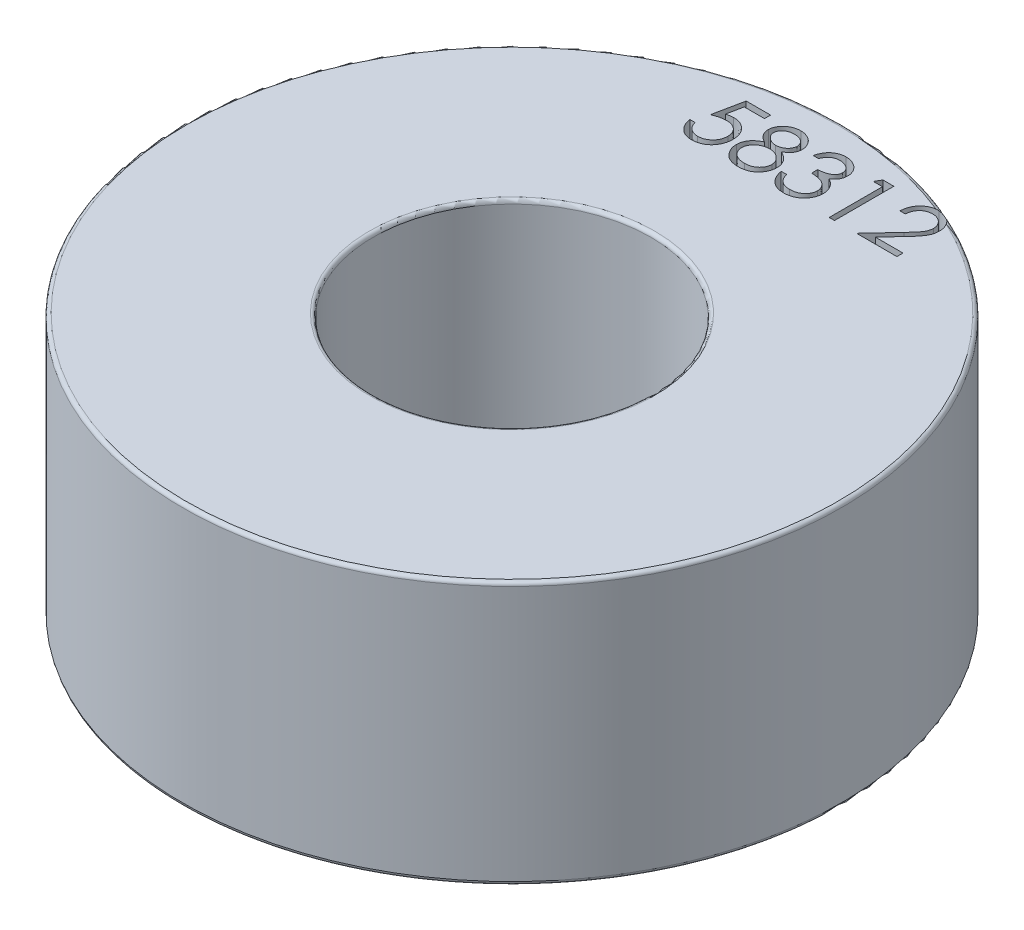
SolidWorks part; units mm, degrees
ref_plane "Front Plane" through (0, 0, 0) normal (0, 0, 1) x (1, 0, 0)
ref_plane "Top Plane" through (0, 0, 0) normal (0, 1, 0) x (1, 0, 0)
ref_plane "Right Plane" through (0, 0, 0) normal (1, 0, 0) x (0, 0, -1)
sketch "Toroidal Core TC229" plane through (0, 0, 0) normal (0, 0, 1) x (1, 0, 0)
  line L0 (0, -8.108) -> (0, 13.3131) construction
  line L2 (5.7191, 0) -> (13.073, 0)
  line L3 (5.573, 0.1461) -> (5.573, 10.3979)
  line L4 (5.7191, 10.5439) -> (13.073, 10.5439)
  line L5 (13.2191, 0.1461) -> (13.2191, 10.3979)
  arc A0 (5.7191, 0) -> (5.573, 0.1461) centre (5.7191, 0.1461) cw
  arc A1 (13.073, 0) -> (13.2191, 0.1461) centre (13.073, 0.1461) ccw
  arc A2 (13.073, 10.5439) -> (13.2191, 10.3979) centre (13.073, 10.3979) cw
  arc A3 (5.573, 10.3979) -> (5.7191, 10.5439) centre (5.7191, 10.3979) cw
  point P9 (5.573, 0)
  point P12 (13.2191, 0)
  point P15 (13.2191, 10.5439)
  point P18 (5.573, 10.5439)
  dimension "D4" = 0.1461
  dimension "D1" = 7.3539
  dimension "D2" = 10.5439
  dimension "D3" = 5.573
revolve "Revolve2" add sketch "Toroidal Core TC229" angle 360 about L0
sketch "Sketch1" plane through (0, 10.5439, 0) normal (0, 1, 0) x (1, 0, 0)
  text T0 "58312" font "Century Gothic" height in points 9
extrude "Cut-Extrude1" cut sketch "Sketch1" against normal blind 1
equation "\"FinishedODmax\"  = 23.7mm"
equation "\"FinishedIDmin\"  = 13.3mm"
equation "\"FinishedHTmax\"  = 8.39mm"
equation "\"FinishedInnerRadiusmin\"= \"FinishedIDmin\" / 2"
equation "\"FinishedOuterRadiusmin\"= \"FinishedODmax\" / 2"
equation "\"Dia18AWG\"= .0424in'Single Build Magnet Wire per http://www.mwswire.com/pdf_files/mws_tech_book/page4_5_6_33_34.pdf"
equation "\"HT\"= \"FinishedHTmax\" + ( \"Dia18AWG\" * 2 )"
equation "\"InnerRadius\"  = \"FinishedInnerRadiusmin\" - ( \"Dia18AWG\" * 1 )"
equation "\"OuterRadius\" = \"FinishedOuterRadiusmin\" + ( \"Dia18AWG\" * 1 )"
equation "\"D2@Toroidal Core TC229\"=\"HT\""
equation "\"D3@Toroidal Core TC229\"=\"InnerRadius\""
equation "\"D1@Toroidal Core TC229\"=\"OuterRadius\"-\"InnerRadius\""
equation "\"Wall\"= \"OuterRadius\" - \"InnerRadius\""
